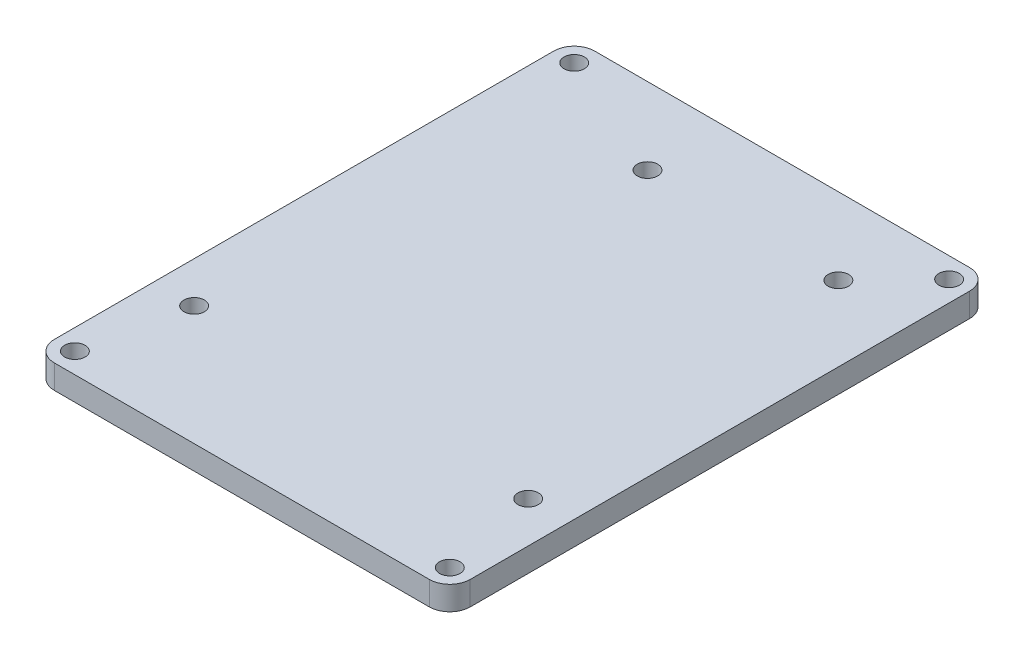
SolidWorks part; units mm, degrees
ref_plane "Front Plane" through (0, 0, 0) normal (0, 0, 1) x (1, 0, 0)
ref_plane "Top Plane" through (0, 0, 0) normal (0, 1, 0) x (1, 0, 0)
ref_plane "Right Plane" through (0, 0, 0) normal (1, 0, 0) x (0, 0, -1)
sketch "Sketch1" plane through (0, 0, 0) normal (0, 1, 0) x (1, 0, 0)
  line L1 (-30.5, 39.625) -> (30.5, 39.625)
  line L2 (-30.5, 39.625) -> (-30.5, -39.625)
  line L3 (-30.5, -39.625) -> (30.5, -39.625)
  line L4 (30.5, 39.625) -> (30.5, -39.625)
  line L5 (-30.5, 39.625) -> (30.5, -39.625) construction
  line L6 (-30.5, -39.625) -> (30.5, 39.625) construction
  point P0 (0, 0)
  dimension "D1" = 61
  dimension "D2" = 79.25
extrude "Boss-Extrude1" add sketch "Sketch1" along normal blind 3.5
sketch "Sketch2" plane through (0, 3.5, 0) normal (0, 1, 0) x (1, 0, 0)
  line L0 (-30.5, 39.625) -> (-30.5, -39.625) construction
  line L1 (30.5, 39.625) -> (-30.5, 39.625) construction
  line L2 (30.5, -39.625) -> (30.5, 39.625) construction
  line L3 (-30.5, -39.625) -> (30.5, -39.625) construction
  circle A0 centre (-27.5, 36.625) radius 1.5
  circle A1 centre (27.5, 36.625) radius 1.5
  circle A2 centre (-27.5, -36.625) radius 1.5
  circle A3 centre (27.5, -36.625) radius 1.5
  dimension "D1" = 3
  dimension "D3" = 3
  dimension "D4" = 3
  dimension "D5" = 3
  dimension "D2" = 3
  dimension "D6" = 3
extrude "Cut-Extrude1" cut sketch "Sketch2" against normal blind 3.5
fillet "Fillet1" radius 3 4 edges at (-30.5, 1.75, -39.625) (30.5, 1.75, -39.625) (30.5, 1.75, 39.625) (-30.5, 1.75, 39.625)
sketch "Sketch3" plane through (0, 3.5, 0) normal (0, 1, 0) x (1, 0, 0)
  line L0 (-30.5, -22.125) -> (30.5, -22.125) construction
  line L1 (-30.5, 36.625) -> (-30.5, -36.625) construction
  line L2 (30.5, -36.625) -> (30.5, 36.625) construction
  line L3 (-27.5, -39.625) -> (27.5, -39.625) construction
  line L4 (0, -39.625) -> (0, 39.625) construction
  line L5 (27.5, 39.625) -> (-27.5, 39.625) construction
  circle A0 centre (-24.5, -22.125) radius 1.5
  circle A1 centre (24.5, -22.125) radius 1.5
  circle A2 centre (19.5, 28.375) radius 1.5
  circle A4 centre (-8.5, 28.375) radius 1.5
  dimension "D2" = 24.5
  dimension "D3" = 24.5
  dimension "D4" = 50.5
  dimension "D6" = 28
  dimension "D1" = 17.5
  dimension "D5" = 5
extrude "Cut-Extrude2" cut sketch "Sketch3" against normal blind 3.5
